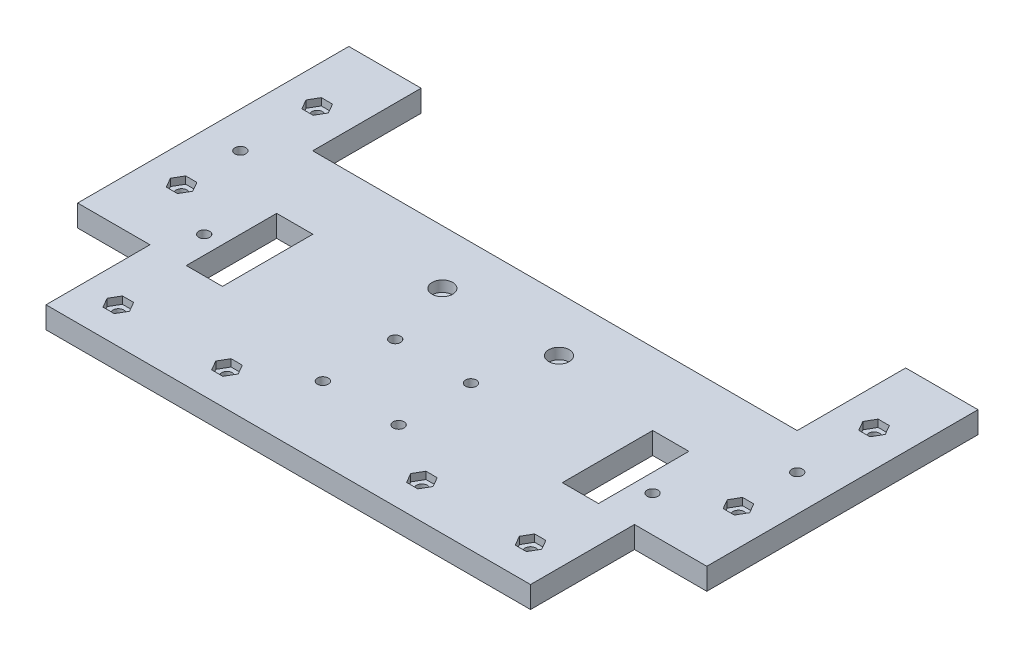
SolidWorks part; units mm, degrees
ref_plane "Alzado" through (0, 0, 0) normal (0, 0, 1) x (1, 0, 0)
ref_plane "Planta" through (0, 0, 0) normal (0, 1, 0) x (1, 0, 0)
ref_plane "Vista lateral" through (0, 0, 0) normal (1, 0, 0) x (0, 0, -1)
sketch "Croquis1" plane through (0, 0, 0) normal (0, 1, 0) x (1, 0, 0)
  line L0 (0, 0) -> (20, 0)
  line L1 (20, 0) -> (20, -30)
  line L2 (20, -30) -> (154, -30)
  line L3 (154, -30) -> (154, 0)
  line L4 (154, 0) -> (174, 0)
  line L5 (174, 0) -> (174, -75)
  line L6 (0, 0) -> (0, -75)
  line L7 (0, -75) -> (20, -75)
  line L8 (174, -75) -> (154, -75)
  line L9 (20, -75) -> (20, -103.75)
  line L10 (20, -103.75) -> (154, -103.75)
  line L11 (154, -103.75) -> (154, -75)
  dimension "D1" = 20
  dimension "D2" = 30
  dimension "D3" = 134
  dimension "D4" = 20
  dimension "D5" = 75
  dimension "D6" = 75
  dimension "D7" = 28.75
extrude "Saliente-Extruir1" add sketch "Croquis1" along normal blind 6
sketch "Croquis2" plane through (0, 6, 0) normal (0, 1, 0) x (1, 0, 0)
  line L0 (0, 0) -> (20, 0) construction
  line L1 (20, 0) -> (10, 0) construction
  line L2 (10, -75) -> (10, -56.25)
  line L3 (0, -75) -> (20, -75) construction
  line L4 (10, -56.25) -> (10, -18.75)
  line L5 (20, -103.75) -> (154, -103.75) construction
  line L6 (13.1, -56.25) -> (11.55, -53.5653)
  line L7 (11.55, -53.5653) -> (8.45, -53.5653)
  line L8 (8.45, -53.5653) -> (6.9, -56.25)
  line L9 (6.9, -56.25) -> (8.45, -58.9347)
  line L10 (8.45, -58.9347) -> (11.55, -58.9347)
  line L11 (11.55, -58.9347) -> (13.1, -56.25)
  line L12 (13.1, -18.75) -> (11.55, -16.0653)
  line L13 (11.55, -16.0653) -> (8.45, -16.0653)
  line L14 (8.45, -16.0653) -> (6.9, -18.75)
  line L15 (6.9, -18.75) -> (8.45, -21.4347)
  line L16 (8.45, -21.4347) -> (11.55, -21.4347)
  line L17 (11.55, -21.4347) -> (13.1, -18.75)
  line L18 (154, -103.75) -> (87, -103.75) construction
  line L19 (87, -103.75) -> (87, -94.1222) construction
  line L20 (162.45, -21.4347) -> (160.9, -18.75)
  line L21 (165.55, -21.4347) -> (162.45, -21.4347)
  line L22 (167.1, -18.75) -> (165.55, -21.4347)
  line L23 (165.55, -16.0653) -> (167.1, -18.75)
  line L24 (162.45, -16.0653) -> (165.55, -16.0653)
  line L25 (160.9, -18.75) -> (162.45, -16.0653)
  line L26 (162.45, -58.9347) -> (160.9, -56.25)
  line L27 (165.55, -58.9347) -> (162.45, -58.9347)
  line L28 (167.1, -56.25) -> (165.55, -58.9347)
  line L29 (165.55, -53.5653) -> (167.1, -56.25)
  line L30 (162.45, -53.5653) -> (165.55, -53.5653)
  line L31 (160.9, -56.25) -> (162.45, -53.5653)
  line L32 (20, -75) -> (30, -75) construction
  line L33 (30, -75) -> (30, -93.75) construction
  line L34 (162.45, -21.4347) -> (160.9, -18.75)
  line L35 (33.1, -93.75) -> (31.55, -91.0653)
  line L36 (31.55, -91.0653) -> (28.45, -91.0653)
  line L37 (28.45, -91.0653) -> (26.9, -93.75)
  line L38 (26.9, -93.75) -> (28.45, -96.4347)
  line L39 (28.45, -96.4347) -> (31.55, -96.4347)
  line L40 (31.55, -96.4347) -> (33.1, -93.75)
  line L41 (165.55, -21.4347) -> (162.45, -21.4347)
  line L42 (167.1, -18.75) -> (165.55, -21.4347)
  line L43 (165.55, -16.0653) -> (167.1, -18.75)
  line L44 (162.45, -16.0653) -> (165.55, -16.0653)
  line L45 (160.9, -18.75) -> (162.45, -16.0653)
  line L46 (162.45, -58.9347) -> (160.9, -56.25)
  line L47 (165.55, -58.9347) -> (162.45, -58.9347)
  line L48 (167.1, -56.25) -> (165.55, -58.9347)
  line L49 (165.55, -53.5653) -> (167.1, -56.25)
  line L50 (162.45, -53.5653) -> (165.55, -53.5653)
  line L51 (160.9, -56.25) -> (162.45, -53.5653)
  line L52 (142.45, -96.4347) -> (140.9, -93.75)
  line L53 (145.55, -96.4347) -> (142.45, -96.4347)
  line L54 (147.1, -93.75) -> (145.55, -96.4347)
  line L55 (145.55, -91.0653) -> (147.1, -93.75)
  line L56 (142.45, -91.0653) -> (145.55, -91.0653)
  line L57 (140.9, -93.75) -> (142.45, -91.0653)
  line L58 (33.1, -93.75) -> (140.9, -93.75) construction
  line L59 (87, -93.75) -> (33.1, -93.75) construction
  line L60 (33.1, -93.75) -> (87, -93.75) construction
  line L61 (87, -93.75) -> (60.05, -93.75) construction
  line L62 (112.4, -96.4347) -> (110.85, -93.75)
  line L63 (63.15, -93.75) -> (61.6, -91.0653)
  line L64 (61.6, -91.0653) -> (58.5, -91.0653)
  line L65 (58.5, -91.0653) -> (56.95, -93.75)
  line L66 (56.95, -93.75) -> (58.5, -96.4347)
  line L67 (58.5, -96.4347) -> (61.6, -96.4347)
  line L68 (61.6, -96.4347) -> (63.15, -93.75)
  line L69 (115.5, -96.4347) -> (112.4, -96.4347)
  line L70 (117.05, -93.75) -> (115.5, -96.4347)
  line L71 (115.5, -91.0653) -> (117.05, -93.75)
  line L72 (112.4, -91.0653) -> (115.5, -91.0653)
  line L73 (110.85, -93.75) -> (112.4, -91.0653)
  circle A0 centre (10, -56.25) radius 3.1 construction
  circle A1 centre (10, -18.75) radius 3.1 construction
  circle A2 centre (30, -93.75) radius 3.1 construction
  circle A3 centre (60.05, -93.75) radius 3.1 construction
  dimension "D1" = 18.75
  dimension "D2" = 37.5
  dimension "D3" = 10
  dimension "D4" = 18.75
extrude "Cortar-Extruir1" cut sketch "Croquis2" against normal blind 2
sketch "Croquis3" plane through (0, 0, 0) normal (0, -1, 0) x (1, 0, 0)
  line L0 (10, 75) -> (10, 56.25) construction
  line L1 (10, 56.25) -> (10, 18.75) construction
  line L2 (162.45, 21.4347) -> (160.9, 18.75) construction
  line L3 (160.9, 18.75) -> (162.45, 16.0653) construction
  line L4 (162.45, 21.4347) -> (160.9, 18.75) construction
  line L5 (160.9, 18.75) -> (162.45, 16.0653) construction
  line L6 (165.55, 21.4347) -> (162.45, 21.4347) construction
  line L7 (165.55, 21.4347) -> (162.45, 21.4347) construction
  line L8 (162.45, 53.5653) -> (165.55, 53.5653) construction
  line L9 (160.9, 56.25) -> (162.45, 53.5653) construction
  line L10 (162.45, 53.5653) -> (165.55, 53.5653) construction
  line L11 (160.9, 56.25) -> (162.45, 53.5653) construction
  line L12 (165.55, 53.5653) -> (167.1, 56.25) construction
  line L13 (165.55, 53.5653) -> (167.1, 56.25) construction
  line L14 (167.1, 56.25) -> (165.55, 58.9347) construction
  line L15 (167.1, 56.25) -> (165.55, 58.9347) construction
  line L16 (165.55, 58.9347) -> (162.45, 58.9347) construction
  line L17 (165.55, 58.9347) -> (162.45, 58.9347) construction
  line L18 (162.45, 58.9347) -> (160.9, 56.25) construction
  line L19 (162.45, 58.9347) -> (160.9, 56.25) construction
  line L20 (162.45, 16.0653) -> (165.55, 16.0653) construction
  line L21 (162.45, 16.0653) -> (165.55, 16.0653) construction
  line L22 (165.55, 16.0653) -> (167.1, 18.75) construction
  line L23 (165.55, 16.0653) -> (167.1, 18.75) construction
  line L24 (167.1, 18.75) -> (165.55, 21.4347) construction
  line L25 (167.1, 18.75) -> (165.55, 21.4347) construction
  line L26 (13.1, 18.75) -> (11.55, 16.0653) construction
  line L27 (11.55, 16.0653) -> (8.45, 16.0653) construction
  line L28 (8.45, 16.0653) -> (6.9, 18.75) construction
  line L29 (6.9, 18.75) -> (8.45, 21.4347) construction
  line L30 (8.45, 21.4347) -> (11.55, 21.4347) construction
  line L31 (11.55, 21.4347) -> (13.1, 18.75) construction
  line L32 (8.45, 58.9347) -> (11.55, 58.9347) construction
  line L33 (6.9, 56.25) -> (8.45, 58.9347) construction
  line L34 (8.45, 53.5653) -> (6.9, 56.25) construction
  line L35 (11.55, 53.5653) -> (8.45, 53.5653) construction
  line L36 (13.1, 56.25) -> (11.55, 53.5653) construction
  line L37 (11.55, 58.9347) -> (13.1, 56.25) construction
  line L38 (142.45, 96.4347) -> (140.9, 93.75) construction
  line L39 (145.55, 96.4347) -> (142.45, 96.4347) construction
  line L40 (147.1, 93.75) -> (145.55, 96.4347) construction
  line L41 (145.55, 91.0653) -> (147.1, 93.75) construction
  line L42 (142.45, 91.0653) -> (145.55, 91.0653) construction
  line L43 (140.9, 93.75) -> (142.45, 91.0653) construction
  line L44 (31.55, 91.0653) -> (28.45, 91.0653) construction
  line L45 (28.45, 91.0653) -> (26.9, 93.75) construction
  line L46 (26.9, 93.75) -> (28.45, 96.4347) construction
  line L47 (28.45, 96.4347) -> (31.55, 96.4347) construction
  line L48 (31.55, 96.4347) -> (33.1, 93.75) construction
  line L49 (33.1, 93.75) -> (31.55, 91.0653) construction
  line L50 (58.5, 91.0653) -> (56.95, 93.75) construction
  line L51 (56.95, 93.75) -> (58.5, 96.4347) construction
  line L52 (58.5, 96.4347) -> (61.6, 96.4347) construction
  line L53 (61.6, 96.4347) -> (63.15, 93.75) construction
  line L54 (63.15, 93.75) -> (61.6, 91.0653) construction
  line L55 (61.6, 91.0653) -> (58.5, 91.0653) construction
  line L56 (112.4, 96.4347) -> (110.85, 93.75) construction
  line L57 (115.5, 96.4347) -> (112.4, 96.4347) construction
  line L58 (117.05, 93.75) -> (115.5, 96.4347) construction
  line L59 (115.5, 91.0653) -> (117.05, 93.75) construction
  line L60 (112.4, 91.0653) -> (115.5, 91.0653) construction
  line L61 (110.85, 93.75) -> (112.4, 91.0653) construction
  line L62 (10, 75) -> (10, 56.25)
  line L63 (10, 56.25) -> (10, 18.75)
  line L64 (162.45, 21.4347) -> (160.9, 18.75)
  line L65 (160.9, 18.75) -> (162.45, 16.0653)
  line L66 (162.45, 21.4347) -> (160.9, 18.75)
  line L67 (160.9, 18.75) -> (162.45, 16.0653)
  line L68 (165.55, 21.4347) -> (162.45, 21.4347)
  line L69 (165.55, 21.4347) -> (162.45, 21.4347)
  line L70 (162.45, 53.5653) -> (165.55, 53.5653)
  line L71 (160.9, 56.25) -> (162.45, 53.5653)
  line L72 (162.45, 53.5653) -> (165.55, 53.5653)
  line L73 (160.9, 56.25) -> (162.45, 53.5653)
  line L74 (165.55, 53.5653) -> (167.1, 56.25)
  line L75 (165.55, 53.5653) -> (167.1, 56.25)
  line L76 (167.1, 56.25) -> (165.55, 58.9347)
  line L77 (167.1, 56.25) -> (165.55, 58.9347)
  line L78 (165.55, 58.9347) -> (162.45, 58.9347)
  line L79 (165.55, 58.9347) -> (162.45, 58.9347)
  line L80 (162.45, 58.9347) -> (160.9, 56.25)
  line L81 (162.45, 58.9347) -> (160.9, 56.25)
  line L82 (162.45, 16.0653) -> (165.55, 16.0653)
  line L83 (162.45, 16.0653) -> (165.55, 16.0653)
  line L84 (165.55, 16.0653) -> (167.1, 18.75)
  line L85 (165.55, 16.0653) -> (167.1, 18.75)
  line L86 (167.1, 18.75) -> (165.55, 21.4347)
  line L87 (167.1, 18.75) -> (165.55, 21.4347)
  line L88 (13.1, 18.75) -> (11.55, 16.0653)
  line L89 (11.55, 16.0653) -> (8.45, 16.0653)
  line L90 (8.45, 16.0653) -> (6.9, 18.75)
  line L91 (6.9, 18.75) -> (8.45, 21.4347)
  line L92 (8.45, 21.4347) -> (11.55, 21.4347)
  line L93 (11.55, 21.4347) -> (13.1, 18.75)
  line L94 (8.45, 58.9347) -> (11.55, 58.9347)
  line L95 (6.9, 56.25) -> (8.45, 58.9347)
  line L96 (8.45, 53.5653) -> (6.9, 56.25)
  line L97 (11.55, 53.5653) -> (8.45, 53.5653)
  line L98 (13.1, 56.25) -> (11.55, 53.5653)
  line L99 (11.55, 58.9347) -> (13.1, 56.25)
  line L100 (142.45, 96.4347) -> (140.9, 93.75)
  line L101 (145.55, 96.4347) -> (142.45, 96.4347)
  line L102 (147.1, 93.75) -> (145.55, 96.4347)
  line L103 (145.55, 91.0653) -> (147.1, 93.75)
  line L104 (142.45, 91.0653) -> (145.55, 91.0653)
  line L105 (140.9, 93.75) -> (142.45, 91.0653)
  line L106 (31.55, 91.0653) -> (28.45, 91.0653)
  line L107 (28.45, 91.0653) -> (26.9, 93.75)
  line L108 (26.9, 93.75) -> (28.45, 96.4347)
  line L109 (28.45, 96.4347) -> (31.55, 96.4347)
  line L110 (31.55, 96.4347) -> (33.1, 93.75)
  line L111 (33.1, 93.75) -> (31.55, 91.0653)
  line L112 (58.5, 91.0653) -> (56.95, 93.75)
  line L113 (56.95, 93.75) -> (58.5, 96.4347)
  line L114 (58.5, 96.4347) -> (61.6, 96.4347)
  line L115 (61.6, 96.4347) -> (63.15, 93.75)
  line L116 (63.15, 93.75) -> (61.6, 91.0653)
  line L117 (61.6, 91.0653) -> (58.5, 91.0653)
  line L118 (112.4, 96.4347) -> (110.85, 93.75)
  line L119 (115.5, 96.4347) -> (112.4, 96.4347)
  line L120 (117.05, 93.75) -> (115.5, 96.4347)
  line L121 (115.5, 91.0653) -> (117.05, 93.75)
  line L122 (112.4, 91.0653) -> (115.5, 91.0653)
  line L123 (110.85, 93.75) -> (112.4, 91.0653)
extrude "Cortar-Extruir2" cut sketch "Croquis3" against normal blind 2
sketch "Croquis4" plane through (0, 6, 0) normal (0, 1, 0) x (1, 0, 0)
  line L0 (10, -75) -> (10, -56.25) construction
  line L1 (10, -56.25) -> (10, -18.75) construction
  line L2 (162.45, -21.4347) -> (160.9, -18.75) construction
  line L3 (160.9, -18.75) -> (162.45, -16.0653) construction
  line L4 (162.45, -21.4347) -> (160.9, -18.75) construction
  line L5 (160.9, -18.75) -> (162.45, -16.0653) construction
  line L6 (165.55, -21.4347) -> (162.45, -21.4347) construction
  line L7 (165.55, -21.4347) -> (162.45, -21.4347) construction
  line L8 (162.45, -53.5653) -> (165.55, -53.5653) construction
  line L9 (160.9, -56.25) -> (162.45, -53.5653) construction
  line L10 (162.45, -53.5653) -> (165.55, -53.5653) construction
  line L11 (160.9, -56.25) -> (162.45, -53.5653) construction
  line L12 (165.55, -53.5653) -> (167.1, -56.25) construction
  line L13 (165.55, -53.5653) -> (167.1, -56.25) construction
  line L14 (167.1, -56.25) -> (165.55, -58.9347) construction
  line L15 (167.1, -56.25) -> (165.55, -58.9347) construction
  line L16 (165.55, -58.9347) -> (162.45, -58.9347) construction
  line L17 (165.55, -58.9347) -> (162.45, -58.9347) construction
  line L18 (162.45, -58.9347) -> (160.9, -56.25) construction
  line L19 (162.45, -58.9347) -> (160.9, -56.25) construction
  line L20 (162.45, -16.0653) -> (165.55, -16.0653) construction
  line L21 (162.45, -16.0653) -> (165.55, -16.0653) construction
  line L22 (165.55, -16.0653) -> (167.1, -18.75) construction
  line L23 (165.55, -16.0653) -> (167.1, -18.75) construction
  line L24 (167.1, -18.75) -> (165.55, -21.4347) construction
  line L25 (167.1, -18.75) -> (165.55, -21.4347) construction
  line L26 (13.1, -18.75) -> (11.55, -16.0653) construction
  line L27 (11.55, -16.0653) -> (8.45, -16.0653) construction
  line L28 (8.45, -16.0653) -> (6.9, -18.75) construction
  line L29 (6.9, -18.75) -> (8.45, -21.4347) construction
  line L30 (8.45, -21.4347) -> (11.55, -21.4347) construction
  line L31 (11.55, -21.4347) -> (13.1, -18.75) construction
  line L32 (8.45, -58.9347) -> (11.55, -58.9347) construction
  line L33 (6.9, -56.25) -> (8.45, -58.9347) construction
  line L34 (8.45, -53.5653) -> (6.9, -56.25) construction
  line L35 (11.55, -53.5653) -> (8.45, -53.5653) construction
  line L36 (13.1, -56.25) -> (11.55, -53.5653) construction
  line L37 (11.55, -58.9347) -> (13.1, -56.25) construction
  line L38 (142.45, -96.4347) -> (140.9, -93.75) construction
  line L39 (145.55, -96.4347) -> (142.45, -96.4347) construction
  line L40 (147.1, -93.75) -> (145.55, -96.4347) construction
  line L41 (145.55, -91.0653) -> (147.1, -93.75) construction
  line L42 (142.45, -91.0653) -> (145.55, -91.0653) construction
  line L43 (140.9, -93.75) -> (142.45, -91.0653) construction
  line L44 (31.55, -91.0653) -> (28.45, -91.0653) construction
  line L45 (28.45, -91.0653) -> (26.9, -93.75) construction
  line L46 (26.9, -93.75) -> (28.45, -96.4347) construction
  line L47 (28.45, -96.4347) -> (31.55, -96.4347) construction
  line L48 (31.55, -96.4347) -> (33.1, -93.75) construction
  line L49 (33.1, -93.75) -> (31.55, -91.0653) construction
  line L50 (58.5, -91.0653) -> (56.95, -93.75) construction
  line L51 (56.95, -93.75) -> (58.5, -96.4347) construction
  line L52 (58.5, -96.4347) -> (61.6, -96.4347) construction
  line L53 (61.6, -96.4347) -> (63.15, -93.75) construction
  line L54 (63.15, -93.75) -> (61.6, -91.0653) construction
  line L55 (61.6, -91.0653) -> (58.5, -91.0653) construction
  line L56 (112.4, -96.4347) -> (110.85, -93.75) construction
  line L57 (115.5, -96.4347) -> (112.4, -96.4347) construction
  line L58 (117.05, -93.75) -> (115.5, -96.4347) construction
  line L59 (115.5, -91.0653) -> (117.05, -93.75) construction
  line L60 (112.4, -91.0653) -> (115.5, -91.0653) construction
  line L61 (110.85, -93.75) -> (112.4, -91.0653) construction
  line L62 (10, -75) -> (10, -56.25)
  line L63 (10, -56.25) -> (10, -18.75)
  line L64 (162.45, -21.4347) -> (160.9, -18.75)
  line L65 (160.9, -18.75) -> (162.45, -16.0653)
  line L66 (162.45, -21.4347) -> (160.9, -18.75)
  line L67 (160.9, -18.75) -> (162.45, -16.0653)
  line L68 (165.55, -21.4347) -> (162.45, -21.4347)
  line L69 (165.55, -21.4347) -> (162.45, -21.4347)
  line L70 (162.45, -53.5653) -> (165.55, -53.5653)
  line L71 (160.9, -56.25) -> (162.45, -53.5653)
  line L72 (162.45, -53.5653) -> (165.55, -53.5653)
  line L73 (160.9, -56.25) -> (162.45, -53.5653)
  line L74 (165.55, -53.5653) -> (167.1, -56.25)
  line L75 (165.55, -53.5653) -> (167.1, -56.25)
  line L76 (167.1, -56.25) -> (165.55, -58.9347)
  line L77 (167.1, -56.25) -> (165.55, -58.9347)
  line L78 (165.55, -58.9347) -> (162.45, -58.9347)
  line L79 (165.55, -58.9347) -> (162.45, -58.9347)
  line L80 (162.45, -58.9347) -> (160.9, -56.25)
  line L81 (162.45, -58.9347) -> (160.9, -56.25)
  line L82 (162.45, -16.0653) -> (165.55, -16.0653)
  line L83 (162.45, -16.0653) -> (165.55, -16.0653)
  line L84 (165.55, -16.0653) -> (167.1, -18.75)
  line L85 (165.55, -16.0653) -> (167.1, -18.75)
  line L86 (167.1, -18.75) -> (165.55, -21.4347)
  line L87 (167.1, -18.75) -> (165.55, -21.4347)
  line L88 (13.1, -18.75) -> (11.55, -16.0653)
  line L89 (11.55, -16.0653) -> (8.45, -16.0653)
  line L90 (8.45, -16.0653) -> (6.9, -18.75)
  line L91 (6.9, -18.75) -> (8.45, -21.4347)
  line L92 (8.45, -21.4347) -> (11.55, -21.4347)
  line L93 (11.55, -21.4347) -> (13.1, -18.75)
  line L94 (8.45, -58.9347) -> (11.55, -58.9347)
  line L95 (6.9, -56.25) -> (8.45, -58.9347)
  line L96 (8.45, -53.5653) -> (6.9, -56.25)
  line L97 (11.55, -53.5653) -> (8.45, -53.5653)
  line L98 (13.1, -56.25) -> (11.55, -53.5653)
  line L99 (11.55, -58.9347) -> (13.1, -56.25)
  line L100 (142.45, -96.4347) -> (140.9, -93.75)
  line L101 (145.55, -96.4347) -> (142.45, -96.4347)
  line L102 (147.1, -93.75) -> (145.55, -96.4347)
  line L103 (145.55, -91.0653) -> (147.1, -93.75)
  line L104 (142.45, -91.0653) -> (145.55, -91.0653)
  line L105 (140.9, -93.75) -> (142.45, -91.0653)
  line L106 (31.55, -91.0653) -> (28.45, -91.0653)
  line L107 (28.45, -91.0653) -> (26.9, -93.75)
  line L108 (26.9, -93.75) -> (28.45, -96.4347)
  line L109 (28.45, -96.4347) -> (31.55, -96.4347)
  line L110 (31.55, -96.4347) -> (33.1, -93.75)
  line L111 (33.1, -93.75) -> (31.55, -91.0653)
  line L112 (58.5, -91.0653) -> (56.95, -93.75)
  line L113 (56.95, -93.75) -> (58.5, -96.4347)
  line L114 (58.5, -96.4347) -> (61.6, -96.4347)
  line L115 (61.6, -96.4347) -> (63.15, -93.75)
  line L116 (63.15, -93.75) -> (61.6, -91.0653)
  line L117 (61.6, -91.0653) -> (58.5, -91.0653)
  line L118 (112.4, -96.4347) -> (110.85, -93.75)
  line L119 (115.5, -96.4347) -> (112.4, -96.4347)
  line L120 (117.05, -93.75) -> (115.5, -96.4347)
  line L121 (115.5, -91.0653) -> (117.05, -93.75)
  line L122 (112.4, -91.0653) -> (115.5, -91.0653)
  line L123 (110.85, -93.75) -> (112.4, -91.0653)
  line L124 (26.9, -93.75) -> (33.1, -93.75) construction
  line L125 (30, -93.75) -> (33.1, -93.75) construction
  line L126 (56.95, -93.75) -> (63.15, -93.75) construction
  line L127 (60.05, -93.75) -> (63.15, -93.75) construction
  line L128 (110.85, -93.75) -> (117.05, -93.75) construction
  line L129 (113.95, -93.75) -> (117.05, -93.75) construction
  line L130 (147.1, -93.75) -> (140.9, -93.75) construction
  line L131 (144, -93.75) -> (140.9, -93.75) construction
  line L132 (160.9, -56.25) -> (167.1, -56.25) construction
  line L133 (164, -56.25) -> (167.1, -56.25) construction
  line L134 (160.9, -18.75) -> (167.1, -18.75) construction
  line L135 (164, -18.75) -> (167.1, -18.75) construction
  circle A0 centre (10, -18.75) radius 1.5
  circle A1 centre (10, -56.25) radius 1.5
  circle A2 centre (30, -93.75) radius 1.5
  circle A3 centre (60.05, -93.75) radius 1.5
  circle A4 centre (113.95, -93.75) radius 1.5
  circle A5 centre (144, -93.75) radius 1.5
  circle A6 centre (164, -56.25) radius 1.5
  circle A7 centre (164, -18.75) radius 1.5
  dimension "D1" = 3
  dimension "D2" = 3
  dimension "D3" = 3
  dimension "D4" = 3
  dimension "D5" = 3
  dimension "D6" = 3
  dimension "D7" = 3
  dimension "D8" = 3
extrude "Cortar-Extruir3" cut sketch "Croquis4" against normal blind 12
sketch "Croquis5" plane through (0, 6, 0) normal (0, 1, 0) x (1, 0, 0)
  circle A0 centre (76.5632, -83.75) radius 1.5
  circle A1 centre (97.5211, -83.75) radius 1.5
extrude "Cortar-Extruir4" cut sketch "Croquis5" against normal blind 10
sketch "Croquis6" plane through (0, 6, 0) normal (0, 1, 0) x (1, 0, 0)
  circle A0 centre (76.5632, -63.7451) radius 1.5
  circle A1 centre (97.5211, -63.75) radius 1.5
extrude "Cortar-Extruir5" cut sketch "Croquis6" against normal blind 10
sketch "Croquis7" plane through (0, 6, 0) normal (0, 1, 0) x (1, 0, 0)
  line L0 (2.5, -75) -> (32.5, -75) construction
  line L1 (0, -75) -> (20, -75) construction
  line L2 (32.5, -75) -> (17.5, -75) construction
  line L3 (17.5, -75) -> (2.5, -75) construction
  line L4 (2.5, -75) -> (10, -75) construction
  line L5 (10, -75) -> (25, -75) construction
  line L6 (25, -75) -> (25, -65) construction
  line L7 (32.5, -30) -> (2.5, -30) construction
  line L8 (154, -30) -> (20, -30) construction
  line L9 (2.5, -30) -> (17.5, -30) construction
  line L10 (17.5, -30) -> (10, -30) construction
  line L11 (10, -30) -> (17.5, -30) construction
  line L12 (17.5, -30) -> (32.5, -30) construction
  line L13 (32.5, -30) -> (25, -30) construction
  line L14 (10, -30) -> (10, -40) construction
  line L15 (108, -103.75) -> (87, -103.75) construction
  line L16 (20, -103.75) -> (154, -103.75) construction
  line L17 (87, -103.75) -> (87, -82.9211) construction
  circle A0 centre (10, -40) radius 1.5
  circle A1 centre (25, -65) radius 1.5
  circle A2 centre (164, -40) radius 1.5
  circle A3 centre (149, -65) radius 1.5
  dimension "D3" = 3
  dimension "D4" = 3
  dimension "D1" = 10
  dimension "D2" = 10
extrude "Cortar-Extruir6" cut sketch "Croquis7" against normal blind 10
sketch "Croquis8" plane through (0, 6, 0) normal (0, 1, 0) x (1, 0, 0)
  line L0 (87, -30) -> (87, -45) construction
  line L1 (154, -30) -> (20, -30) construction
  line L2 (87, -45) -> (103.13, -45)
  line L3 (87, -45) -> (70.87, -45)
  circle A0 centre (70.87, -45) radius 2.85
  circle A1 centre (103.13, -45) radius 2.85
  dimension "D4" = 5.7
  dimension "D5" = 5.7
  dimension "D1" = 15
  dimension "D2" = 16.13
  dimension "D3" = 16.13
extrude "Cortar-Extruir7" cut sketch "Croquis8" against normal blind 3 contours A1 | A0
sketch "Croquis9" plane through (0, 3, 0) normal (0, 1, 0) x (1, 0, 0)
  circle A0 centre (70.87, -45) radius 2.85 construction
  circle A1 centre (70.87, -45) radius 2.85
  circle A2 centre (70.87, -45) radius 1.5
  circle A4 centre (103.13, -45) radius 1.5
  dimension "D1" = 3
  dimension "D3" = 3
extrude "Cortar-Extruir9" cut sketch "Croquis9" against normal blind 13 contours A2 | A4
sketch "Croquis10" plane through (0, 0, 0) normal (0, -1, 0) x (1, 0, 0)
  line L0 (154, 30) -> (144, 30) construction
  line L1 (154, 30) -> (20, 30) construction
  line L2 (154, 0) -> (154, 30) construction
  line L3 (144, 30) -> (144, 49.9561) construction
  line L4 (87, 30) -> (87, 37.7103) construction
  line L5 (144, 49.9561) -> (134, 49.9561)
  line L6 (144, 49.9561) -> (144, 74.9561)
  line L7 (144, 74.9561) -> (134, 74.9561)
  line L8 (134, 49.9561) -> (134, 74.9561)
  line L9 (30, 49.9561) -> (40, 49.9561)
  line L10 (30, 74.9561) -> (40, 74.9561)
  line L11 (30, 49.9561) -> (30, 74.9561)
  line L12 (40, 49.9561) -> (40, 74.9561)
  dimension "D1" = 10
extrude "Cortar-Extruir10" cut sketch "Croquis10" against normal blind 11.3
